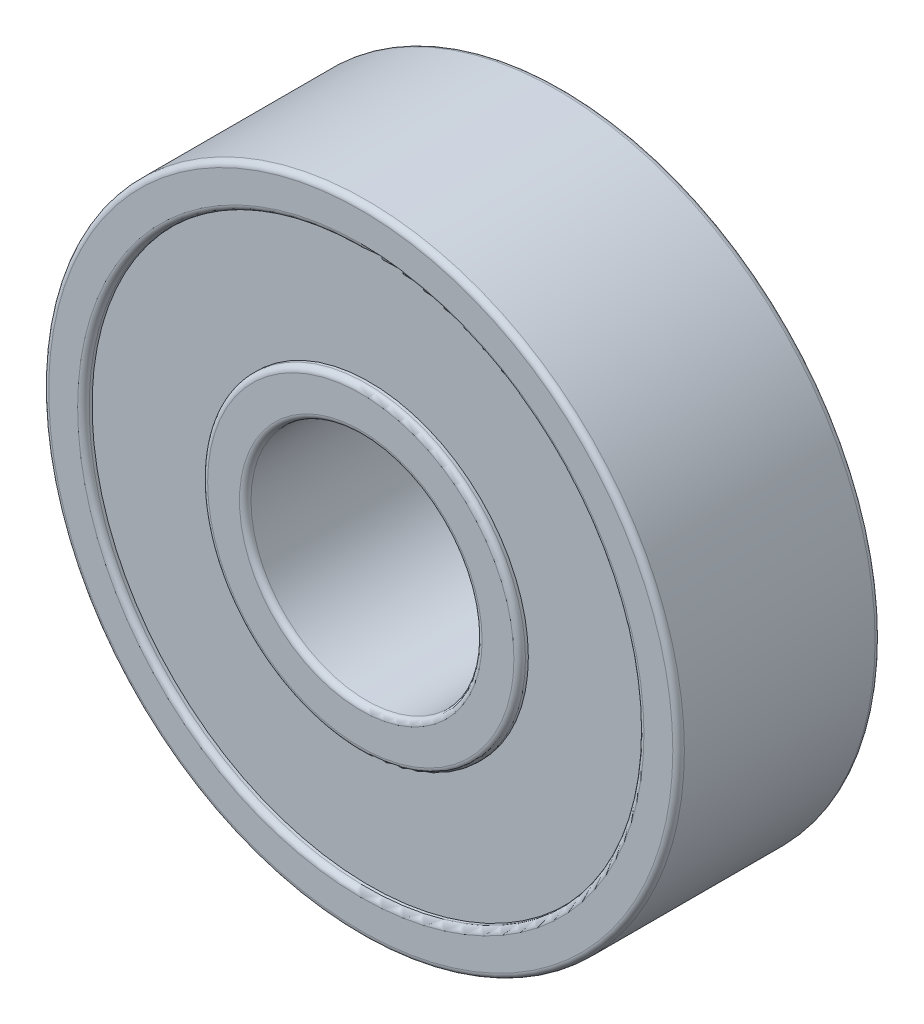
SolidWorks part; units mm, degrees
ref_plane "Front Plane" through (0, 0, 0) normal (0, 0, 1) x (1, 0, 0)
ref_plane "Top Plane" through (0, 0, 0) normal (0, 1, 0) x (1, 0, 0)
ref_plane "Right Plane" through (0, 0, 0) normal (1, 0, 0) x (0, 0, -1)
sketch "Sketch1" plane through (0, 0, 0) normal (0, 0, 1) x (1, 0, 0)
  circle A0 centre (0, 0) radius 11
  circle A1 centre (0, 0) radius 4
  dimension "D1" = 22
  dimension "D2" = 8
extrude "Boss-Extrude1" add sketch "Sketch1" along normal mid plane 7
sketch "Sketch2" plane through (0, 0, 0) normal (1, 0, 0) x (0, 0, -1)
  line L0 (3.2, 9.6) -> (3.5, 9.6)
  line L1 (3.5, 9.6) -> (3.5, 5.5)
  line L2 (3.5, 5.5) -> (3.2, 5.5)
  line L3 (3.2, 5.5) -> (3.2, 9.6)
  line L4 (3.5, 5.5) -> (3.5, 4) construction
  line L5 (3.5, 11) -> (3.5, 9.6) construction
  line L6 (-8.1816, 0) -> (10.3298, 0) construction
  dimension "D1" = 1.5
  dimension "D2" = 1.4
  dimension "D3" = 0.3
revolve "Cut-Revolve1" cut sketch "Sketch2" angle 360 about L6
mirror "Mirror1" about plane through (0, 0, 0) normal (0, 0, 1) of "Cut-Revolve1"
fillet "Fillet1" radius 0.2 8 edges at (9.6, 0, 3.5) (4, 0, 3.5) (5.5, 0, 3.5) (4, 0, -3.5) (5.5, 0, -3.5) (9.6, 0, -3.5) (11, 0, 3.5) (11, 0, -3.5)
